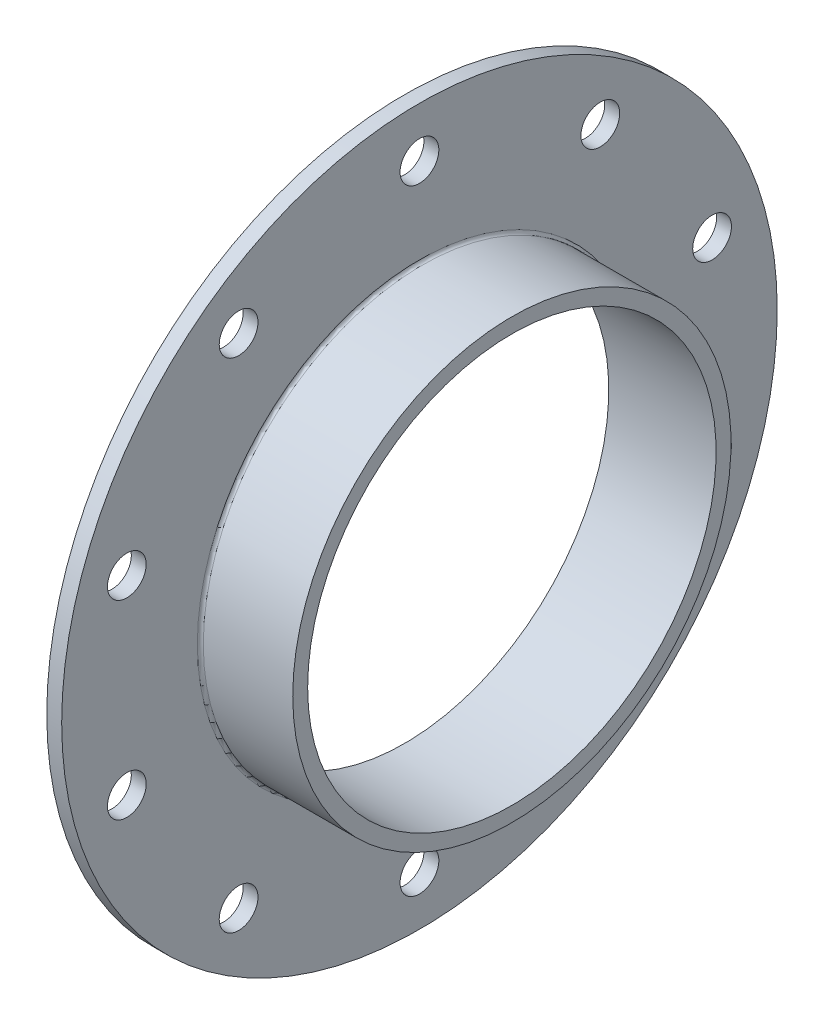
SolidWorks part; units mm, degrees
material "AISI 316 Stainless Steel Sheet (SS)"
ref_plane "Front Plane" through (0, 0, 0) normal (0, 0, 1) x (1, 0, 0)
ref_plane "Top Plane" through (0, 0, 0) normal (0, 1, 0) x (1, 0, 0)
ref_plane "Right Plane" through (0, 0, 0) normal (1, 0, 0) x (0, 0, -1)
sketch "Sketch3" plane through (0, 0, 0) normal (0, 0, 1) x (1, 0, 0)
  line L0 (0, 0) -> (54.1304, 0) construction
  line L1 (0, 34.25) -> (0, 60)
  line L2 (0, 60) -> (2.5, 60)
  line L3 (2.5, 60) -> (2.5, 36.75)
  line L4 (2.5, 36.75) -> (18, 36.75)
  line L5 (18, 36.75) -> (18, 34.25)
  line L6 (18, 34.25) -> (0, 34.25)
  dimension "D1" = 18
  dimension "D2" = 2.5
  dimension "D3" = 2.5
  dimension "D4" = 34.25
  dimension "D5" = 25.75
revolve "Revolve1" add sketch "Sketch3" angle 360 about L0
ref_plane "Plane1" through (0, 0, 0) normal (-1, 0, 0) x (0, 0, 1)
sketch "Sketch4" plane through (0, 0, 0) normal (-1, 0, 0) x (0, 0, 1)
  line L0 (0, 34.25) -> (0, 60) construction
  line L1 (0, 0) -> (0, 51.6) construction
  circle A0 centre (30.3297, 41.7453) radius 3.25
  circle A1 centre (0, 51.6) radius 3.25
  circle A2 centre (49.0745, 15.9453) radius 3.25
  circle A3 centre (49.0745, -15.9453) radius 3.25
  circle A4 centre (30.3297, -41.7453) radius 3.25
  circle A5 centre (0, -51.6) radius 3.25
  circle A6 centre (-30.3297, -41.7453) radius 3.25
  circle A7 centre (-49.0745, -15.9453) radius 3.25
  circle A8 centre (-49.0745, 15.9453) radius 3.25
  circle A9 centre (-30.3297, 41.7453) radius 3.25
  point P22 (0, 0)
  dimension "D2" = 6.5
  dimension "D3" = 8.4
  dimension "D1" = 10
extrude "Cut-Extrude1" cut sketch "Sketch4" against normal blind 10
sketch "Sketch5" plane through (0, 0, 0) normal (0, 0, 1) x (1, 0, 0)
  line L0 (2.5, 36.75) -> (18, 36.75) construction
  point P0 (12, 36.75)
  dimension "D1" = 6
ref_plane "Plane2" through (12, 0, 0) normal (1, 0, 0) x (0, 0, -1)
sketch "Sketch6" plane through (12, 0, 0) normal (1, 0, 0) x (0, 0, -1)
  line L0 (0, 0) -> (23.3559, 37.1494)
  line L1 (0, 0) -> (-40.6402, 25.5506)
  dimension "D1" = 90
fillet "Fillet2" radius 0.5 1 edges at (2.5, 0, 36.75)
equation "\"D5@Sketch3\"=60-\"D4@Sketch3\""
equation "\"D4@Sketch3\"=69/2-0.25"
